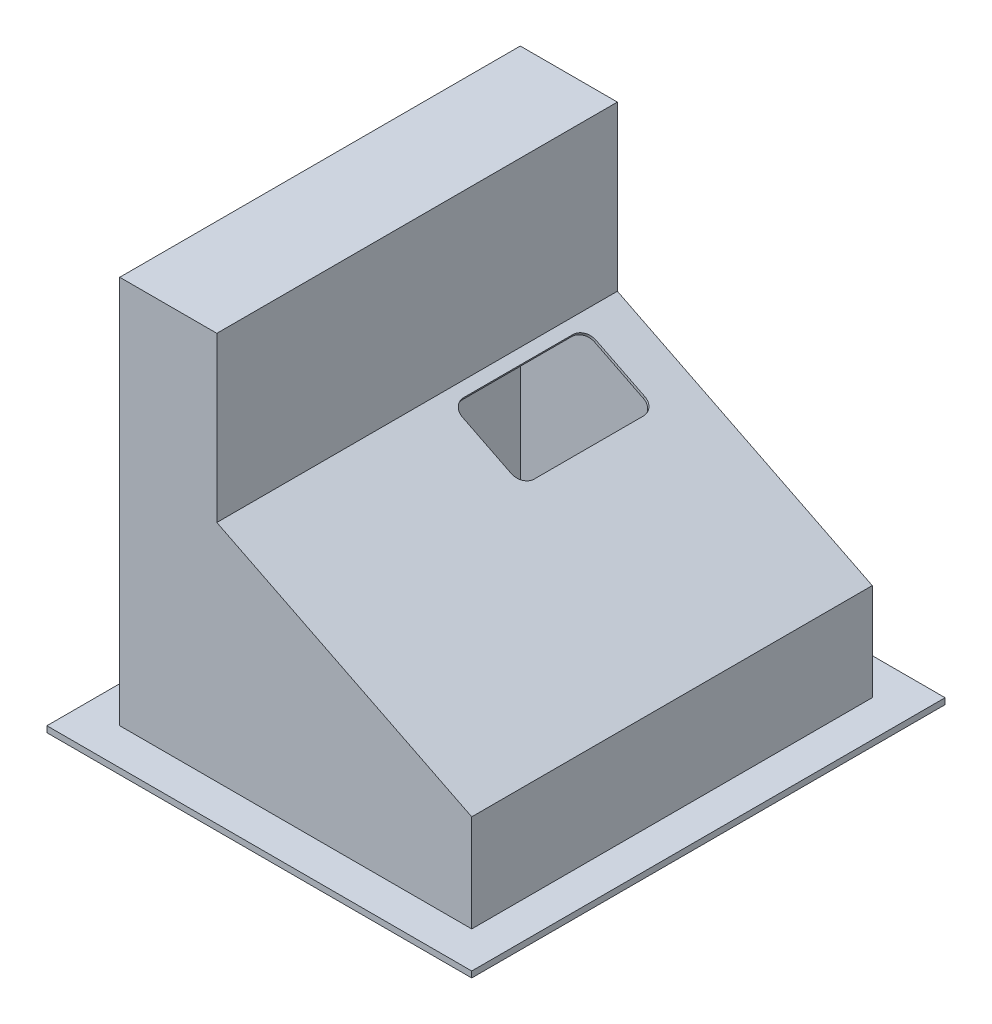
SolidWorks part; units mm, degrees
ref_plane "Front" through (0, 0, 0) normal (0, 0, 1) x (1, 0, 0)
ref_plane "Top" through (0, 0, 0) normal (0, 1, 0) x (1, 0, 0)
ref_plane "Right" through (0, 0, 0) normal (1, 0, 0) x (0, 0, -1)
sketch "Sketch1" plane through (0, 0, 0) normal (0, 0, 1) x (1, 0, 0)
  line L0 (101.6, 0) -> (101.6, 25.4)
  line L1 (101.6, 25.4) -> (34.925, 58.7375)
  line L2 (101.6, 0) -> (111.125, 0)
  line L3 (0, 0) -> (9.525, 0)
  line L4 (9.525, 0) -> (9.525, 101.6)
  line L5 (9.525, 101.6) -> (34.925, 101.6)
  line L6 (34.925, 101.6) -> (34.925, 58.7375)
  line L7 (0, 0) -> (0, -1.5875)
  line L8 (0, -1.5875) -> (11.1125, -1.5875)
  line L9 (11.1125, -1.5875) -> (11.1125, 100.0125)
  line L10 (11.1125, 100.0125) -> (33.3375, 100.0125)
  line L11 (33.3375, 100.0125) -> (33.3375, 58.7375)
  line L12 (33.3375, 58.7375) -> (100.0125, 25.4)
  line L13 (100.0125, 25.4) -> (100.0125, -1.5875)
  line L14 (100.0125, -1.5875) -> (111.125, -1.5875)
  line L15 (111.125, -1.5875) -> (111.125, 0)
extrude "Extrude1" add sketch "Sketch1" along normal blind 101.6
sketch "Sketch2" plane through (0, 0, 101.6) normal (0, 0, 1) x (1, 0, 0)
  line L0 (0, 0) -> (9.525, 0)
  line L1 (9.525, 0) -> (9.525, 101.6)
  line L2 (9.525, 101.6) -> (34.925, 101.6)
  line L3 (34.925, 101.6) -> (34.925, 58.7375)
  line L4 (34.925, 58.7375) -> (101.6, 25.4)
  line L5 (101.6, 25.4) -> (101.6, 0)
  line L6 (101.6, 0) -> (111.125, 0)
  line L7 (111.125, 0) -> (111.125, -1.5875)
  line L8 (111.125, -1.5875) -> (0, -1.5875)
  line L9 (0, -1.5875) -> (0, 0)
extrude "Extrude2" add sketch "Sketch2" along normal blind 1.5875
sketch "Sketch3" plane through (0, 0, 0) normal (0, 0, -1) x (-1, 0, 0)
  line L0 (-111.125, -1.5875) -> (-111.125, 0)
  line L1 (-111.125, 0) -> (-101.6, 0)
  line L2 (-101.6, 0) -> (-101.6, 25.4)
  line L3 (-101.6, 25.4) -> (-34.925, 58.7375)
  line L4 (-34.925, 58.7375) -> (-34.925, 101.6)
  line L5 (-34.925, 101.6) -> (-9.525, 101.6)
  line L6 (-9.525, 101.6) -> (-9.525, 0)
  line L7 (-9.525, 0) -> (0, 0)
  line L8 (0, 0) -> (0, -1.5875)
  line L9 (0, -1.5875) -> (-111.125, -1.5875)
extrude "Extrude3" add sketch "Sketch3" along normal blind 1.5875
sketch "Sketch4" plane through (0, 0, 103.1875) normal (0, 0, 1) x (1, 0, 0)
  line L0 (0, 0) -> (111.125, 0)
  line L1 (111.125, 0) -> (111.125, -1.5875)
  line L2 (111.125, -1.5875) -> (0, -1.5875)
  line L3 (0, -1.5875) -> (0, 0)
extrude "Extrude4" add sketch "Sketch4" along normal blind 9.525
sketch "Sketch5" plane through (0, 0, -1.5875) normal (0, 0, -1) x (-1, 0, 0)
  line L0 (-111.125, 0) -> (0, 0)
  line L1 (0, 0) -> (0, -1.5875)
  line L2 (0, -1.5875) -> (-111.125, -1.5875)
  line L3 (-111.125, -1.5875) -> (-111.125, 0)
extrude "Extrude5" add sketch "Sketch5" along normal blind 9.525
sketch "Sketch6" plane through (30.1625, 60.325, 0) normal (-0.4472, -0.8944, 0) x (0.8944, -0.4472, 0)
  line L0 (75.663, 101.6) -> (75.663, 0)
  line L1 (10.6493, 101.6) -> (90.1639, 101.6) construction
  line L2 (90.1639, 0) -> (10.6493, 0) construction
  line L3 (75.663, 0) -> (78.0947, 0)
  line L4 (78.0947, 0) -> (78.0947, 101.6)
  line L5 (78.0947, 101.6) -> (75.663, 101.6)
extrude "Extrude6" add sketch "Sketch6" along normal blind 25.4
sketch "Sketch8" plane through (69.85, -34.925, 0) normal (0.8944, -0.4472, 0) x (0, 0, -1)
  line L0 (-101.6, 67.4454) -> (0, 67.4454) construction
  circle A0 centre (-50.8, 51.6354) radius 2.5
  dimension "D1" = 15.81
extrude "Cut-Extrude1" cut sketch "Sketch8" against normal blind 1.5875
sketch "Sketch9" plane through (30.48, 60.96, 0) normal (0.4472, 0.8944, 0) x (-0.8944, 0.4472, 0)
  line L0 (-25.4, 44.45) -> (-11.1125, 44.45)
  line L1 (-7.9375, 41.275) -> (-7.9375, 12.7)
  line L2 (-11.1125, 9.525) -> (-25.4, 9.525)
  line L3 (-28.575, 12.7) -> (-28.575, 41.275)
  arc A2 (-25.4, 44.45) -> (-28.575, 41.275) centre (-25.4, 41.275) ccw
  arc A4 (-28.575, 12.7) -> (-25.4, 9.525) centre (-25.4, 12.7) ccw
  arc A5 (-7.9375, 12.7) -> (-11.1125, 9.525) centre (-11.1125, 12.7) cw
  arc A6 (-11.1125, 44.45) -> (-7.9375, 41.275) centre (-11.1125, 41.275) cw
extrude "Cut-Extrude2" cut sketch "Sketch9" against normal blind 3
